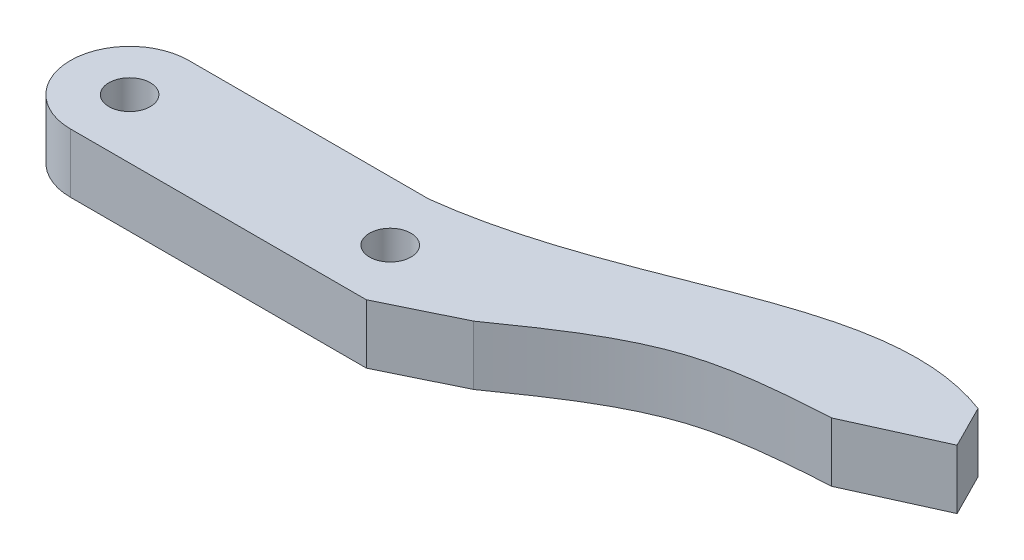
SolidWorks part; units mm, degrees
ref_plane "Front Plane" through (0, 0, 0) normal (0, 0, 1) x (1, 0, 0)
ref_plane "Top Plane" through (0, 0, 0) normal (0, 1, 0) x (1, 0, 0)
ref_plane "Right Plane" through (0, 0, 0) normal (1, 0, 0) x (0, 0, -1)
sketch "Sketch1" plane through (0, 0, 0) normal (0, 1, 0) x (1, 0, 0)
  line L1 (-5, 5) -> (27, 5)
  line L2 (-5, 5) -> (-5, -5)
  line L3 (-5, -5) -> (27, -5)
  line L4 (27, 5) -> (27, -5)
  line L5 (-5, 5) -> (27, -5) construction
  line L6 (-5, -5) -> (27, 5) construction
  circle A0 centre (0, 0) radius 5
  circle A1 centre (0, 0) radius 1.75
  circle A2 centre (22, 0) radius 1.75
  circle A3 centre (22, 0) radius 5
  point P7 (11, 0)
  point P12 (0, 0)
  dimension "D1" = 10
  dimension "D2" = 22
  dimension "D3" = 3.5
extrude "Boss-Extrude1" add sketch "Sketch1" along normal blind 5 contours A0 A1 | A3 L1 A0 L3 | A3 A2
sketch "Sketch2" plane through (0, 5, 0) normal (0, 1, 0) x (1, 0, 0)
  line L0 (22, -5) -> (24.99, -5)
  line L1 (24.99, -5) -> (31.08, -2.0297)
  line L2 (0, 5) -> (22, 5) construction
  line L4 (58.75, 12.87) -> (60.557, 9.3014)
  line L5 (60.557, 9.3014) -> (53.27, 6)
  line L6 (0, -5) -> (22, -5) construction
  line L7 (11, 5) -> (22, 5)
  circle A0 centre (22, 0) radius 1.75 construction
  arc A1 (22, -5) -> (22, 5) centre (22, 0) ccw construction
  arc A2 (22, -5) -> (22, 5) centre (22, 0) ccw
  spline S0 degree 3 poles (11, 5) (31.6706, 2.4222) (44.4109, 18.2251) (58.75, 12.87) knots 0 0 0 0 1 1 1 1
  spline S1 degree 3 poles (31.08, -2.0297) (34.7498, 0.5503) (41.4511, 5.2618) (49.5887, 5.7701) (53.27, 6) knots 0 0 0 0 0.547617 1 1 1 1
  point P2 (0, 0)
  point P16 (61.6858, 10.1332)
  point P17 (34.7713, 12.9919)
  point P18 (0, 0)
  point P19 (0, 0)
  point P20 (32.3845, 10.1332)
  point P21 (0, 0)
  point P22 (0, 0)
  point P23 (33.1988, 10.1332)
  point P24 (41.8969, 5.0162)
  arc M7 (22, -5) -> (22, 5) centre (22, 0) ccw
  line M8 (22, 5) -> (0, 5)
  dimension "D1" = 4
  dimension "D2" = 8
  dimension "D3" = 17.87
  dimension "D4" = 11
  dimension "D5" = 26
  dimension "D6" = 47.75
  dimension "D7" = 2.99
  dimension "D8" = 9.08
  dimension "D9" = 13.52
  dimension "D10" = 20.52
  dimension "D11" = 31.27
  dimension "D12" = 9.45
extrude "Boss-Extrude2" add sketch "Sketch2" against normal blind 5 contours L1 S1 L5 L4 S0 L0 M8 M7
